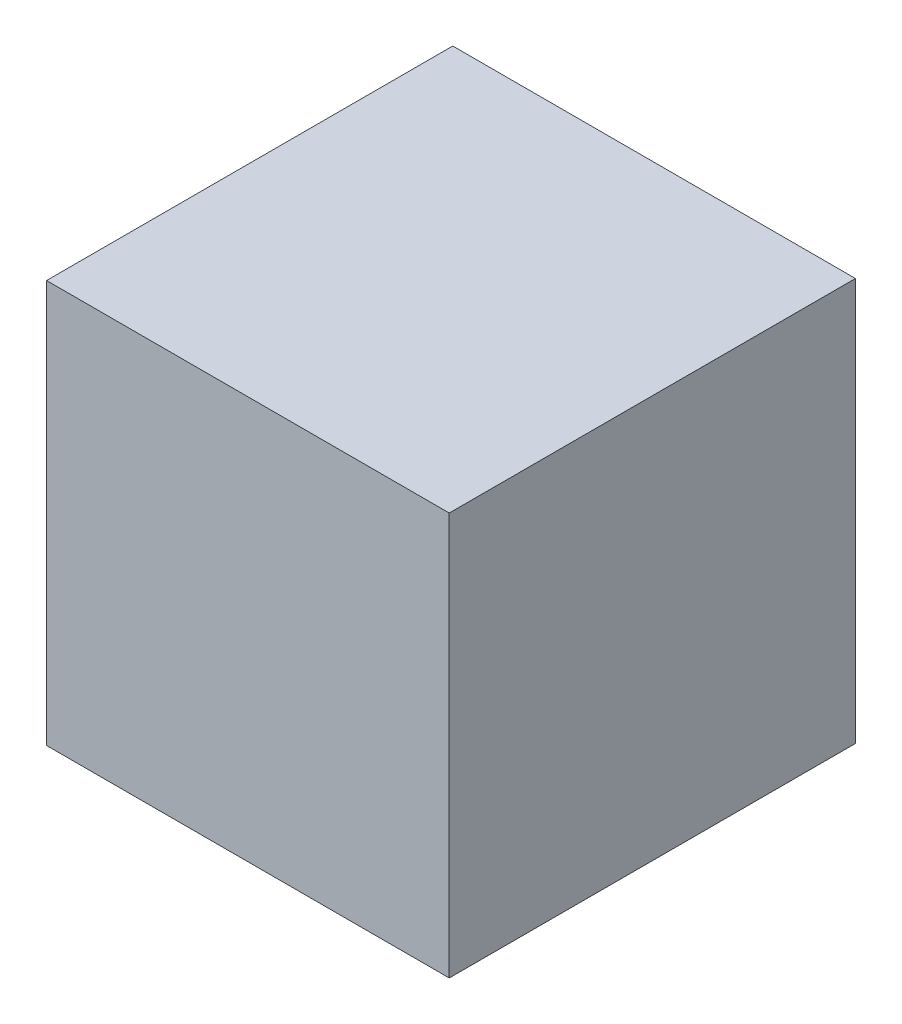
SolidWorks part; units mm, degrees
ref_plane "Front Plane" through (0, 0, 0) normal (0, 0, 1) x (1, 0, 0)
ref_plane "Top Plane" through (0, 0, 0) normal (0, 1, 0) x (1, 0, 0)
ref_plane "Right Plane" through (0, 0, 0) normal (1, 0, 0) x (0, 0, -1)
sketch "Sketch1" plane through (0, 0, 0) normal (0, 0, 1) x (1, 0, 0)
  line L1 (0, 0) -> (20, 0)
  line L2 (0, 0) -> (0, 20)
  line L3 (0, 20) -> (20, 20)
  line L4 (20, 0) -> (20, 20)
extrude "Boss-Extrude1" add sketch "Sketch1" along normal blind 20.1745
equation "\"A\" = atn(1)"
equation "\"D1@Boss-Extrude1\" = 20 + 10 * sin(1)"
